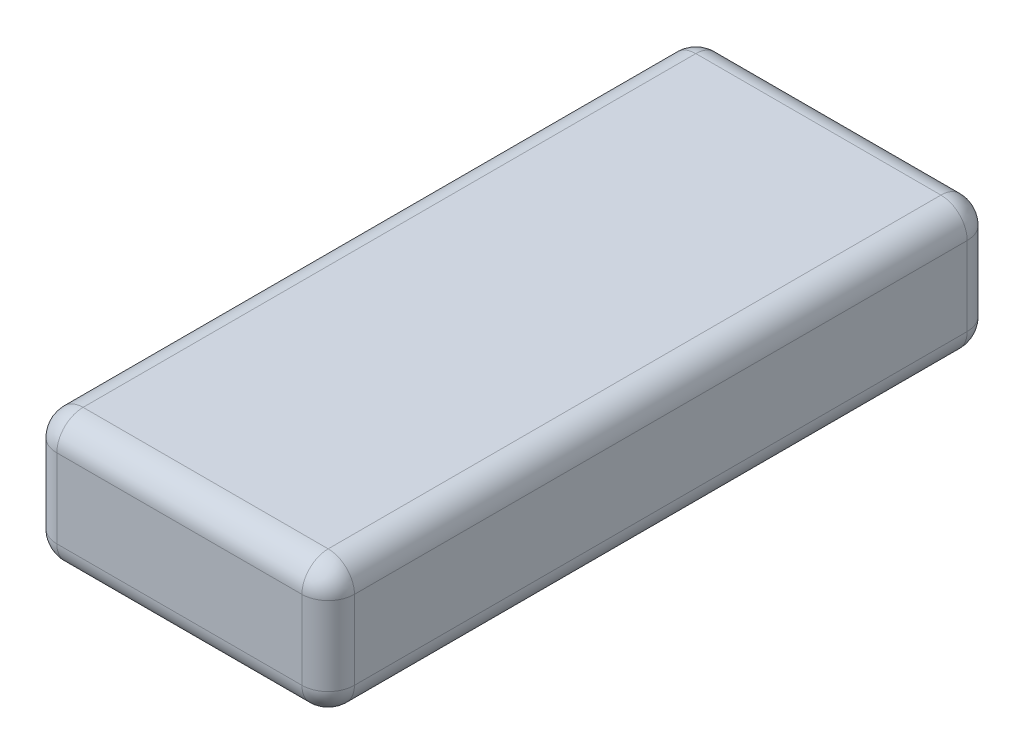
SolidWorks part; units mm, degrees
ref_plane "Front Plane" through (0, 0, 0) normal (0, 0, 1) x (1, 0, 0)
ref_plane "Top Plane" through (0, 0, 0) normal (0, 1, 0) x (1, 0, 0)
ref_plane "Right Plane" through (0, 0, 0) normal (1, 0, 0) x (0, 0, -1)
sketch "Sketch1" plane through (0, 0, 0) normal (0, 1, 0) x (1, 0, 0)
  line L1 (-17, 38) -> (17, 38)
  line L2 (-17, 38) -> (-17, -38)
  line L3 (-17, -38) -> (17, -38)
  line L4 (17, 38) -> (17, -38)
  line L5 (-17, 38) -> (17, -38) construction
  line L6 (-17, -38) -> (17, 38) construction
  point P0 (0, 0)
  dimension "D1" = 76
  dimension "D2" = 34
extrude "Boss-Extrude1" add sketch "Sketch1" along normal blind 15
fillet "Fillet1" radius 3 12 edges at (-17, 7.5, -38) (-17, 7.5, 38) (17, 7.5, 38) (17, 7.5, -38) (0, 0, -38) (-17, 0, 0) (0, 0, 38) (17, 0, 0) (0, 15, 38) (-17, 15, 0) (0, 15, -38) (17, 15, 0)
